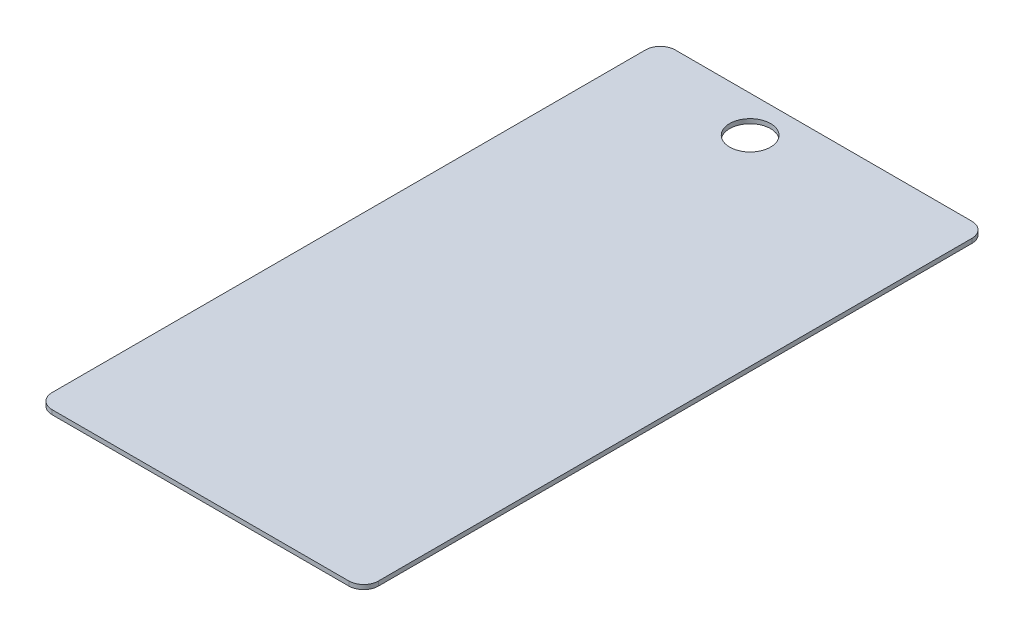
SolidWorks part; units mm, degrees
ref_plane "Спереди" through (0, 0, 0) normal (0, 0, 1) x (1, 0, 0)
ref_plane "Сверху" through (0, 0, 0) normal (0, 1, 0) x (1, 0, 0)
ref_plane "Справа" through (0, 0, 0) normal (1, 0, 0) x (0, 0, -1)
sketch "Sketch1" plane through (0, 0, 0) normal (0, 1, 0) x (1, 0, 0)
  line L0 (-10.68, 20.48) -> (9.32, 20.48)
  line L1 (-11.68, 19.48) -> (-11.68, -20.52)
  line L2 (-10.68, -21.52) -> (9.32, -21.52)
  line L3 (10.32, 19.48) -> (10.32, -20.52)
  arc A0 (10.32, 19.48) -> (9.32, 20.48) centre (9.32, 19.48) ccw
  arc A1 (10.32, -20.52) -> (9.32, -21.52) centre (9.32, -20.52) cw
  arc A2 (-11.68, -20.52) -> (-10.68, -21.52) centre (-10.68, -20.52) ccw
  arc A3 (-11.68, 19.48) -> (-10.68, 20.48) centre (-10.68, 19.48) cw
  dimension "D1" = 1
  dimension "D2" = 22
  dimension "D3" = 42
extrude "Boss-Extrude1" add sketch "Sketch1" along normal blind 0.3
sketch "Sketch5" plane through (0, 0.3, 0) normal (0, 1, 0) x (1, 0, 0)
  circle A0 centre (-3.1696, 18.0201) radius 1.3778
extrude "Cut-Extrude1" cut sketch "Sketch5" against normal up to next
